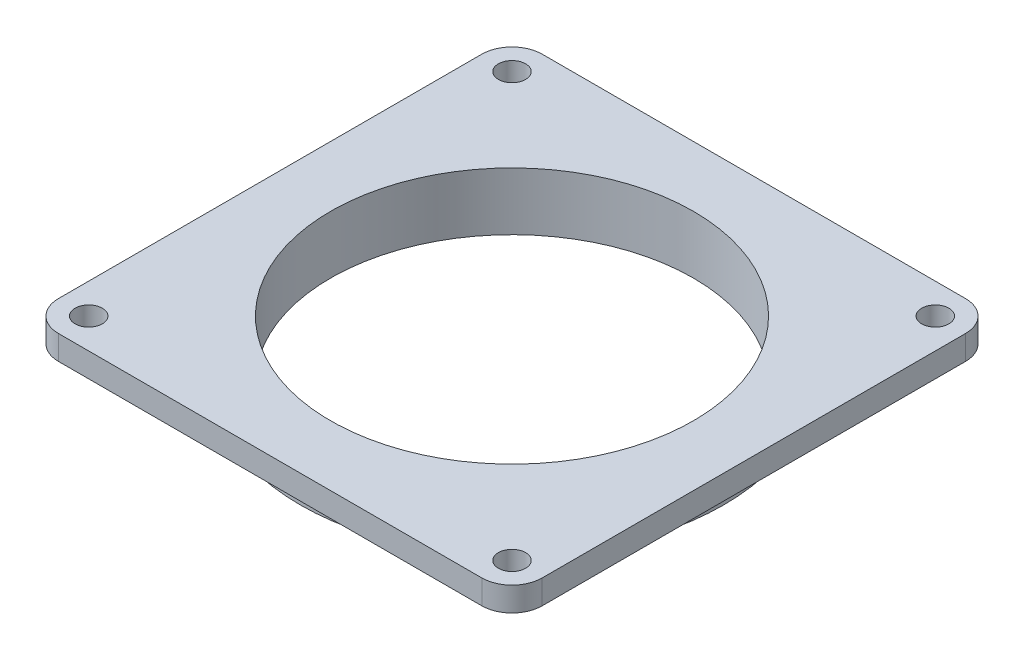
SolidWorks part; units mm, degrees
ref_plane "Front Plane" through (0, 0, 0) normal (0, 0, 1) x (1, 0, 0)
ref_plane "Top Plane" through (0, 0, 0) normal (0, 1, 0) x (1, 0, 0)
ref_plane "Right Plane" through (0, 0, 0) normal (1, 0, 0) x (0, 0, -1)
sketch "Sketch1" plane through (0, 0, 0) normal (0, 1, 0) x (1, 0, 0)
  circle A0 centre (0, 0) radius 35
  circle A1 centre (0, 0) radius 30
extrude "Boss-Extrude1" add sketch "Sketch1" along normal blind 5.5626
sketch "Sketch2" plane through (0, 5.5626, 0) normal (0, 1, 0) x (1, 0, 0)
  line L1 (35, -35) -> (-35, -35)
  line L2 (35, -35) -> (35, 35)
  line L3 (35, 35) -> (-35, 35)
  line L4 (-35, -35) -> (-35, 35)
  line L5 (35, -35) -> (-35, 35) construction
  line L6 (35, 35) -> (-35, -35) construction
  line L7 (40, -40) -> (-40, -40)
  line L8 (40, -40) -> (40, 40)
  line L9 (40, 40) -> (-40, 40)
  line L10 (-40, -40) -> (-40, 40)
  line L11 (40, -40) -> (-40, 40) construction
  line L12 (40, 40) -> (-40, -40) construction
  circle A0 centre (-35, 35) radius 2.25
  circle A1 centre (35, 35) radius 2.25
  circle A2 centre (35, -35) radius 2.25
  circle A3 centre (-35, -35) radius 2.25
  circle A4 centre (0, 0) radius 30
  point P0 (0, 0)
  point P6 (0, 0)
  circle M7 centre (0, 0) radius 35
  circle M8 centre (0, 0) radius 30
  dimension "D1" = 70
  dimension "D2" = 70
  dimension "D3" = 5
  dimension "D4" = 5
extrude "Boss-Extrude3" add sketch "Sketch2" along normal blind 4 contours M7 M8 | A0 L4 L3 M7 | A1 L3 L2 M7 | A2 L2 L1 M7 | A3 L1 L4 M7 | L10 L7 L8 L9 A3 L4 A0 L3 A1 L2 A2 L1
fillet "Fillet1" radius 5 4 edges at (40, 7.5626, 40) (-40, 7.5626, 40) (-40, 7.5626, -40) (40, 7.5626, -40)
